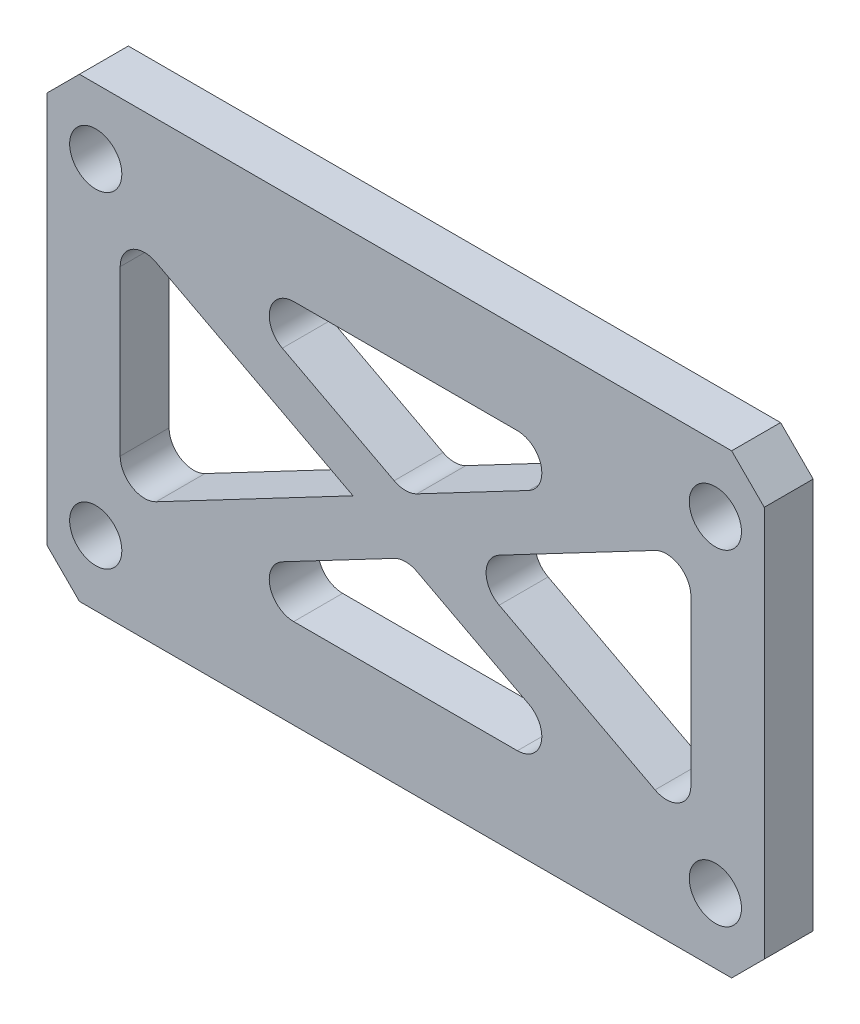
SolidWorks part; units mm, degrees
material "Thornel Mat VMA"
ref_plane "前视基准面" through (0, 0, 0) normal (0, 0, 1) x (1, 0, 0)
ref_plane "上视基准面" through (0, 0, 0) normal (0, 1, 0) x (1, 0, 0)
ref_plane "右视基准面" through (0, 0, 0) normal (1, 0, 0) x (0, 0, -1)
sketch "草图1" plane through (0, 0, 0) normal (0, 0, 1) x (1, 0, 0)
  line L1 (-19, 10) -> (19, 10) construction
  line L2 (-19, 10) -> (-19, -10) construction
  line L3 (-19, -10) -> (19, -10) construction
  line L4 (19, 10) -> (19, -10) construction
  line L5 (-19, 10) -> (19, -10) construction
  line L6 (-19, -10) -> (19, 10) construction
  line L7 (-22, 14) -> (22, 14)
  line L8 (-22, 14) -> (-22, -14)
  line L9 (-22, -14) -> (22, -14)
  line L10 (22, 14) -> (22, -14)
  line L11 (-22, 14) -> (22, -14) construction
  line L12 (-22, -14) -> (22, 14) construction
  circle A0 centre (-19, 10) radius 1.6
  circle A1 centre (-19, -10) radius 1.6
  circle A2 centre (19, -10) radius 1.6
  circle A3 centre (19, 10) radius 1.6
  point P0 (0, 0)
  point P6 (0, 0)
  dimension "D5" = 3.2
  dimension "D1" = 20
  dimension "D2" = 38
  dimension "D3" = 44
  dimension "D4" = 28
extrude "凸台-拉伸1" add sketch "草图1" along normal blind 3
sketch "草图2" plane through (0, 0, 3) normal (0, 0, 1) x (1, 0, 0)
  line L0 (-19, -10) -> (19, 10) construction
  line L1 (-19, 10) -> (19, -10) construction
  line L2 (-19, -10) -> (19, 10)
  line L3 (-19, 10) -> (19, -10)
  line L4 (19, 10) -> (19, -10) construction
  line L5 (-19, -10) -> (19, -10) construction
  line L6 (-19, 10) -> (19, 10) construction
  line L7 (-19, 10) -> (-19, -10) construction
  line L8 (19, 10) -> (19, -10)
  line L9 (-19, -10) -> (19, -10)
  line L10 (-19, 10) -> (19, 10)
  line L11 (-19, 10) -> (-19, -10)
  line L12 (-19.6986, 8.6726) -> (18.3014, -11.3274)
  line L13 (-18.3014, -11.3274) -> (19.6986, 8.6726)
  line L14 (-20.5, 10) -> (-20.5, -10)
  line L15 (-19, -11.5) -> (19, -11.5)
  line L16 (17.5, 10) -> (17.5, -10)
  line L17 (-19, 8.5) -> (19, 8.5)
  line L18 (-18.3014, 11.3274) -> (19.6986, -8.6726)
  line L19 (-19.6986, -8.6726) -> (18.3014, 11.3274)
  line L20 (-17.5, 10) -> (-17.5, -10)
  line L21 (-19, -8.5) -> (19, -8.5)
  line L22 (20.5, 10) -> (20.5, -10)
  line L23 (-19, 11.5) -> (19, 11.5)
  dimension "D1" = 1.5
  dimension "D2" = 1.5
extrude "切除-拉伸1" cut sketch "草图2" against normal blind 3 contours L12 L20 L19 | L18 L19 L17 | L13 L21 L12 | L13 L18 L16
fillet "圆角1" radius 1.5 11 edges at (17.5, 7.5155, 1.5) (17.5, -7.5155, 1.5) (3.2206, 0, 1.5) (12.9294, -8.5, 1.5) (0, -1.6951, 1.5) (-12.9294, -8.5, 1.5) (-17.5, -7.5155, 1.5) (-17.5, 7.5155, 1.5) (0, 1.6951, 1.5) (12.9294, 8.5, 1.5) (-12.9294, 8.5, 1.5)
chamfer "倒角1" distance 2 angle 45 4 edges at (22, -14, 1.5) (-22, -14, 1.5) (-22, 14, 1.5) (22, 14, 1.5)
